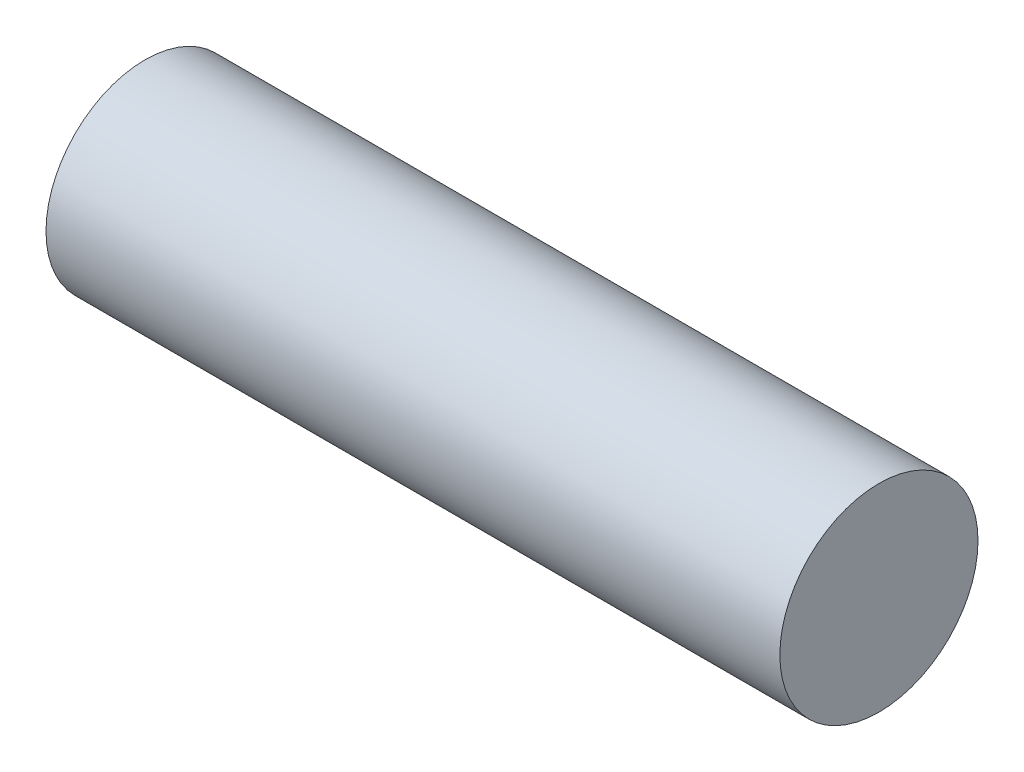
SolidWorks part; units mm, degrees
ref_plane "Front Plane" through (0, 0, 0) normal (0, 0, 1) x (1, 0, 0)
ref_plane "Top Plane" through (0, 0, 0) normal (0, 1, 0) x (1, 0, 0)
ref_plane "Right Plane" through (0, 0, 0) normal (1, 0, 0) x (0, 0, -1)
sketch "Sketch1" plane through (0, 0, 0) normal (1, 0, 0) x (0, 0, -1)
  circle A0 centre (0, 0) radius 13.5
  dimension "D1" = 27
extrude "Boss-Extrude1" add sketch "Sketch1" along normal mid plane 100
sketch "Sketch2" plane through (-50, 0, 0) normal (-1, 0, 0) x (0, 0, 1)
  circle A0 centre (0, 10) radius 1.25
  circle A1 centre (0, 0) radius 13.5 construction
  circle A2 centre (8.6603, 5) radius 1.25
  circle A3 centre (8.6603, -5) radius 1.25
  circle A4 centre (0, -10) radius 1.25
  circle A5 centre (-8.6603, -5) radius 1.25
  circle A6 centre (-8.6603, 5) radius 1.25
  point P17 (0, 0)
  dimension "D1" = 2.5
  dimension "D2" = 10
  dimension "D3" = 6
extrude "Cut-Extrude1" cut sketch "Sketch2" against normal blind 4
